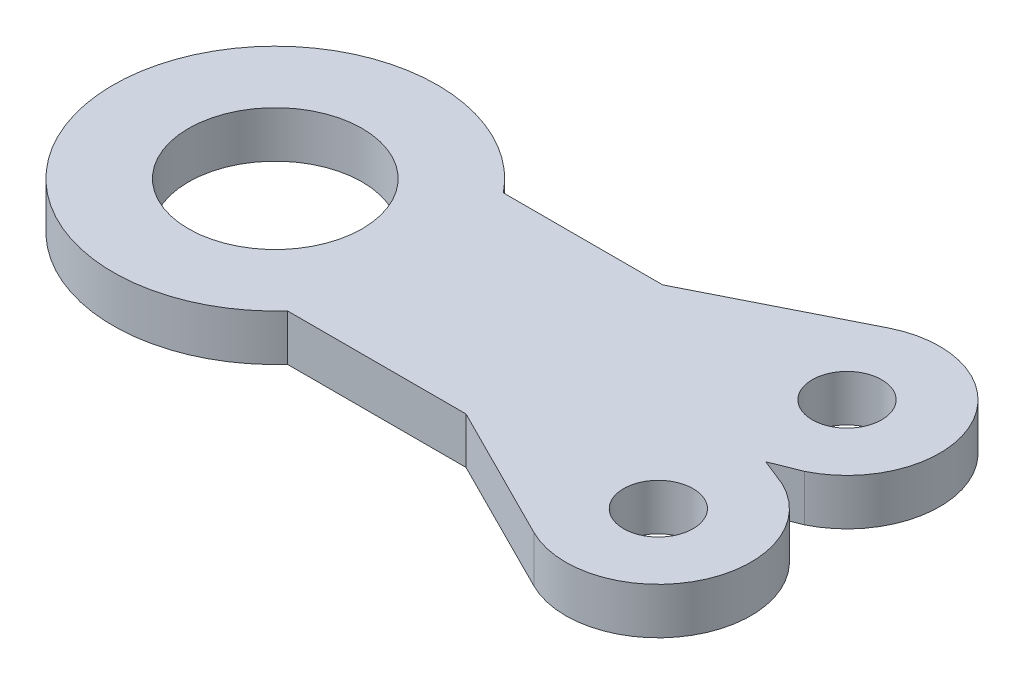
SolidWorks part; units mm, degrees
ref_plane "Front Plane" through (0, 0, 0) normal (0, 0, 1) x (1, 0, 0)
ref_plane "Top Plane" through (0, 0, 0) normal (0, 1, 0) x (1, 0, 0)
ref_plane "Right Plane" through (0, 0, 0) normal (1, 0, 0) x (0, 0, -1)
sketch "Sketch1" plane through (0, 0, 0) normal (0, 1, 0) x (1, 0, 0)
  circle A0 centre (0, 0) radius 7
  dimension "D1" = 14
extrude "Boss-Extrude1" add sketch "Sketch1" along normal blind 2
sketch "Sketch2" plane through (0, 2, 0) normal (0, 1, 0) x (1, 0, 0)
  circle A0 centre (0, 0) radius 3.75
  dimension "D1" = 7.5
extrude "Cut-Extrude1" cut sketch "Sketch2" against normal through all
sketch "Sketch3" plane through (0, 2, 0) normal (0, 1, 0) x (1, 0, 0)
  line L0 (0, 0) -> (18.4714, 0) construction
  line L2 (20.6, 0.8513) -> (20.6, 0) construction
  line L3 (0, -7) -> (0, 7) construction
  line L4 (18.4714, 0) -> (12.5068, 0) construction
  line L5 (15.4891, 1.4999) -> (20.6, 4.0705) construction
  line L6 (20.6, 4.0705) -> (20.6, 2.5705) construction
  line L7 (12.329, 4.388) -> (18.8027, 7.6439)
  line L12 (21.1644, 0) -> (22.3562, 0.4766)
  line L13 (12.329, 4.388) -> (5.4539, 4.388)
  line L14 (12.9098, -4.6801) -> (5.2054, -4.6801)
  line L15 (21.1644, 0) -> (22.3562, -0.4766)
  line L16 (12.9098, -4.6801) -> (18.8027, -7.6439)
  circle A0 centre (20.6, 4.0705) radius 1.5
  circle A1 centre (0, 0) radius 7 construction
  circle A2 centre (20.6, -4.0705) radius 1.5
  arc A3 (22.3562, 0.4766) -> (18.8027, 7.6439) centre (20.6, 4.0705) ccw
  arc A6 (22.3562, -0.4766) -> (18.8027, -7.6439) centre (20.6, -4.0705) cw
  circle A9 centre (0, 0) radius 7
  point P4 (0, 0)
  dimension "D2" = 3
  dimension "D1" = 18.4714
  dimension "D3" = 26.7
  dimension "D6" = 8.1409
extrude "Boss-Extrude2" add sketch "Sketch3" against normal blind 2
